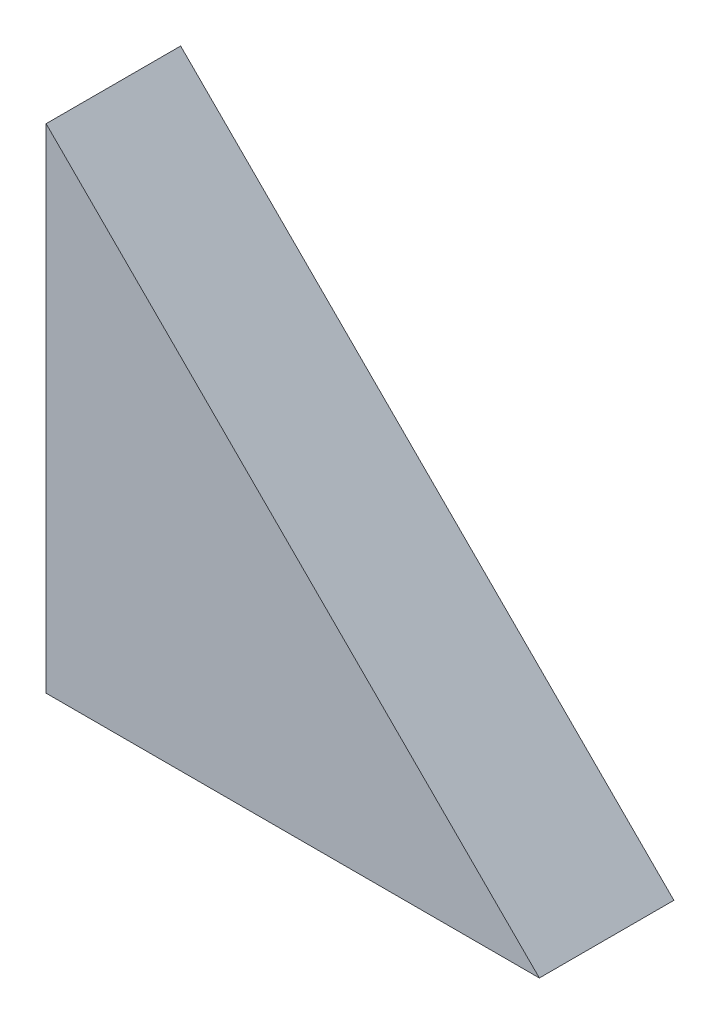
SolidWorks part; units mm, degrees
material "MDF"
ref_plane "Alzado" through (0, 0, 0) normal (0, 0, 1) x (1, 0, 0)
ref_plane "Planta" through (0, 0, 0) normal (0, 1, 0) x (1, 0, 0)
ref_plane "Vista lateral" through (0, 0, 0) normal (1, 0, 0) x (0, 0, -1)
sketch "Croquis1" plane through (0, 0, 0) normal (0, 0, 1) x (1, 0, 0)
  line L0 (0, 0) -> (0, 11)
  line L1 (0, 11) -> (11, 0)
  line L2 (11, 0) -> (0, 0)
  dimension "D1" = 11
extrude "Saliente-Extruir1" add sketch "Croquis1" along normal mid plane 3
